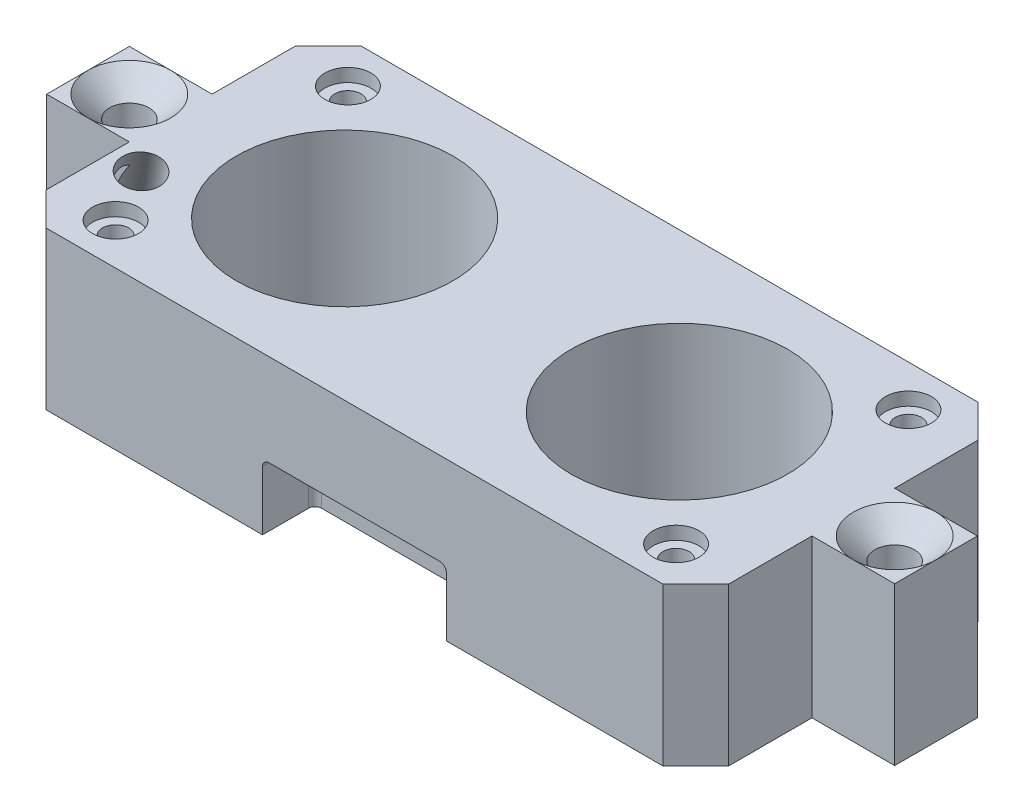
SolidWorks part; units mm, degrees
ref_plane "Front Plane" through (0, 0, 0) normal (0, 0, 1) x (1, 0, 0)
ref_plane "Top Plane" through (0, 0, 0) normal (0, 1, 0) x (1, 0, 0)
ref_plane "Right Plane" through (0, 0, 0) normal (1, 0, 0) x (0, 0, -1)
sketch "Sketch1" plane through (0, 0, 0) normal (0, 1, 0) x (1, 0, 0)
  line L0 (-12.75, 0) -> (12.75, 0) construction
  line L1 (-26, 12) -> (26, 12)
  line L2 (-26, 12) -> (-26, -12)
  line L3 (-26, -12) -> (26, -12)
  line L4 (26, 12) -> (26, -12)
  line L5 (-26, 12) -> (26, -12) construction
  line L6 (-26, -12) -> (26, 12) construction
  circle A0 centre (12.75, 0) radius 8.25
  circle A1 centre (-12.75, 0) radius 8.25
  point P0 (0, 0)
  point P9 (0, 0)
  dimension "D3" = 16.5
  dimension "D1" = 52
  dimension "D2" = 24
  dimension "D4" = 25.5
extrude "Boss-Extrude1" add sketch "Sketch1" along normal blind 12
sketch "Sketch2" plane through (0, 12, 0) normal (0, 1, 0) x (1, 0, 0)
  line L1 (-21.35, 8.85) -> (21.35, 8.85) construction
  line L2 (-21.35, 8.85) -> (-21.35, -8.85) construction
  line L3 (-21.35, -8.85) -> (21.35, -8.85) construction
  line L4 (21.35, 8.85) -> (21.35, -8.85) construction
  line L5 (-21.35, 8.85) -> (21.35, -8.85) construction
  line L6 (-21.35, -8.85) -> (21.35, 8.85) construction
  circle A0 centre (-21.35, 8.85) radius 1
  circle A1 centre (21.35, 8.85) radius 1
  circle A2 centre (21.35, -8.85) radius 1
  circle A3 centre (-21.35, -8.85) radius 1
  point P0 (0, 0)
  dimension "D3" = 2
  dimension "D1" = 17.7
  dimension "D2" = 42.7
extrude "Cut-Extrude1" cut sketch "Sketch2" against normal through all
sketch "Sketch3" plane through (0, 12, 0) normal (0, 1, 0) x (1, 0, 0)
  circle A20 centre (-21.35, 8.85) radius 1.75
  circle A21 centre (21.35, 8.85) radius 1.75
  circle A23 centre (21.35, -8.85) radius 1.75
  circle A24 centre (-21.35, -8.85) radius 1.75
  dimension "D1" = 3.5
extrude "Cut-Extrude2" cut sketch "Sketch3" against normal blind 1
sketch "Sketch4" plane through (0, 0, 0) normal (0, -1, 0) x (1, 0, 0)
  line L0 (26, -12) -> (-26, -12) construction
  line L1 (-6, -12) -> (6, -12)
  line L2 (-6, -12) -> (-6, -5)
  line L3 (-6, -5) -> (6, -5)
  line L4 (6, -12) -> (6, -5)
  line L5 (0, -5) -> (0, 0)
  line M14 (-26, -12) -> (26, -12)
  dimension "D1" = 7
  dimension "D2" = 12
extrude "Cut-Extrude3" cut sketch "Sketch4" against normal blind 5 contours L4 L3 L2 M14
fillet "Fillet3" radius 0.5 5 edges at (-6, 5, -8.5) (6, 5, -8.5) (6, 2.5, -5) (0, 5, -5) (-6, 2.5, -5)
chamfer "Chamfer1" distance 2.5 4 edges at (26, 6, 12) (26, 6, -12) (-26, 6, -12) (-26, 6, 12)
sketch "Sketch5" plane through (0, 0, 0) normal (0, -1, 0) x (1, 0, 0)
  line L0 (-23.5, 12) -> (23.5, 12) construction
  line L1 (-7, 16) -> (7, 16)
  line L2 (-7, 16) -> (-7, 8)
  line L3 (-7, 8) -> (7, 8)
  line L4 (7, 16) -> (7, 8)
  line L5 (-7, 16) -> (7, 8) construction
  line L6 (-7, 8) -> (7, 16) construction
  point P0 (0, 12)
  dimension "D1" = 8
  dimension "D2" = 14
extrude "Cut-Extrude4" cut sketch "Sketch5" against normal up to surface (5 mm away) up to face at (0, 5, -8.75)
fillet "Fillet4" radius 0.5 5 edges at (7, 2.5, 8) (7, 5, 10) (-7, 5, 10) (-7, 2.5, 8) (0, 5, 8)
sketch "Sketch6" plane through (0, 12, 0) normal (0, 1, 0) x (1, 0, 0)
  line L0 (-26, 3.15) -> (-32.3, 3.15)
  line L1 (-26, 9.5) -> (-26, -9.5) construction
  line L2 (-32.3, 3.15) -> (-32.3, -3.15)
  line L3 (-32.3, -3.15) -> (-26, -3.15)
  line L4 (-32.3, -3.15) -> (-26, -3.15) construction
  line L5 (-26, -3.15) -> (-26, 3.15)
  line L6 (-32.3, 3.15) -> (-26, 3.15) construction
  line L8 (26, 3.15) -> (32.3, 3.15)
  line L9 (26, -9.5) -> (26, 9.5) construction
  line L10 (32.3, 3.15) -> (26, 3.15) construction
  line L11 (32.3, 3.15) -> (32.3, -3.15)
  line L12 (32.3, -3.15) -> (26, -3.15)
  line L13 (26, -3.15) -> (26, 3.15)
extrude "Boss-Extrude2" add sketch "Sketch6" against normal up to vertex (12 mm away)
hole_wizard "CSK for M3 SFHCS1" positions "Sketch7" profile "Sketch8" countersink size "M3" standard "ANSI Metric" end condition through all
sketch "Sketch7" plane through (1490.3777, 12, 7.8258) normal (0, 1, 0) x (0.766, 0, -0.6428)
  line L0 (-1161.4085, 984.7533) -> (-1111.922, 943.2292)
  line L6 (-1156.9707, 985.1415) -> (-1161.0202, 980.3154)
  line L11 (-1112.3103, 947.667) -> (-1116.3598, 942.8409)
  point P2 (-1114.3351, 945.254)
  point P48 (-1158.9954, 982.7285)
sketch "Sketch8" plane through (29.15, 12, 0) normal (1, 0, 0) x (0, 0, 1)
  line L0 (0, 0) -> (0, 12)
  line L1 (0, 12) -> (1.5, 12)
  line L2 (1.5, 12) -> (1.5, 1.65)
  line L3 (1.5, 1.65) -> (3.15, 0)
  line L4 (3.15, 0) -> (0, 0)
  line L5 (-1.5, 1.65) -> (-3.15, 0) construction
  line L6 (0, -6.35) -> (0, 107.95) construction
  dimension "Thru Hole Dia." = 3
  dimension "Thru Hole Depth" = 12
  dimension "Near C'Sink Dia." = 6.3
  dimension "Near C'Sink Angle" = 90
hole_wizard "CSK for M3 SFHCS2" positions "Sketch9" profile "Sketch10" countersink size "M3" standard "ANSI Metric"
sketch "Sketch9" plane through (-1373.8349, 567.7831, 105.6168) normal (-0.4295, -0.828, -0.3604) x (-0.6343, 0.5607, -0.5322)
  line L0 (-1161.4085, 984.7533) -> (-1111.922, 943.2292)
  line L6 (-1156.9707, 985.1415) -> (-1161.0202, 980.3154)
  line L11 (-1112.3103, 947.667) -> (-1116.3598, 942.8409)
  point P2 (-1114.3351, 945.254)
  point P48 (-1158.9954, 982.7285)
sketch "Sketch10" plane through (-59.4044, -57.0036, -25.3865) normal (0.5862, -0.5592, 0.5862) x (0.6869, -0.0405, -0.7256)
  line L0 (0, 0) -> (0, 109.9989)
  line L1 (0, 109.9989) -> (1.5, 109.9989)
  line L2 (1.5, 109.9989) -> (1.5, 1.65)
  line L3 (1.5, 1.65) -> (3.15, 0)
  line L4 (3.15, 0) -> (0, 0)
  line L5 (-1.5, 1.65) -> (-3.15, 0) construction
  line L6 (0, -6.35) -> (0, 107.95) construction
  dimension "Thru Hole Dia." = 3
  dimension "Thru Hole Depth" = 109.9989
  dimension "Near C'Sink Dia." = 6.3
  dimension "Near C'Sink Angle" = 90
